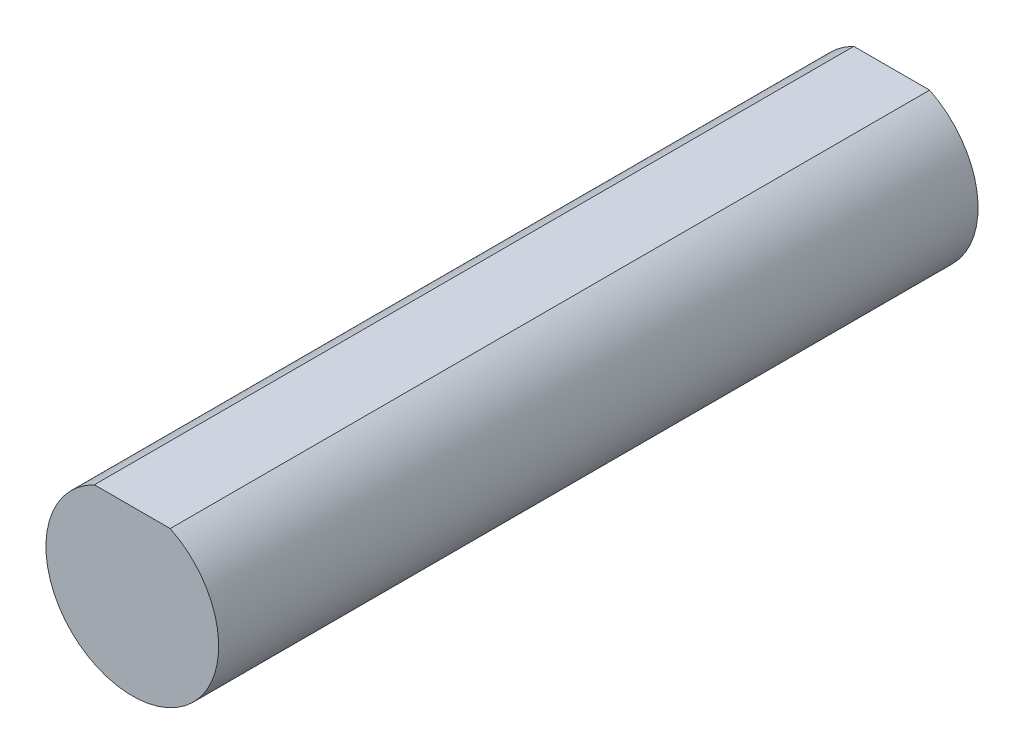
SolidWorks part; units mm, degrees
ref_plane "Front Plane" through (0, 0, 0) normal (0, 0, 1) x (1, 0, 0)
ref_plane "Top Plane" through (0, 0, 0) normal (0, 1, 0) x (1, 0, 0)
ref_plane "Right Plane" through (0, 0, 0) normal (1, 0, 0) x (0, 0, -1)
sketch "Sketch1" plane through (0, 0, 0) normal (0, 0, 1) x (1, 0, 0)
  circle A0 centre (0, 0) radius 2.5019
  dimension "D1" = 5.0038
extrude "Boss-Extrude1" add sketch "Sketch1" along normal blind 21.9964
sketch "Sketch3" plane through (0, 0, 21.9964) normal (0, 0, 1) x (1, 0, 0)
  line L0 (-1.0984, 2.2479) -> (1.0984, 2.2479)
  circle A0 centre (0, 0) radius 2.5019 construction
  arc A1 (-1.0984, 2.2479) -> (1.0984, 2.2479) centre (0, 0) cw
  dimension "D1" = 2.2479
extrude "Cut-Extrude5" cut sketch "Sketch3" against normal blind 21.9964
